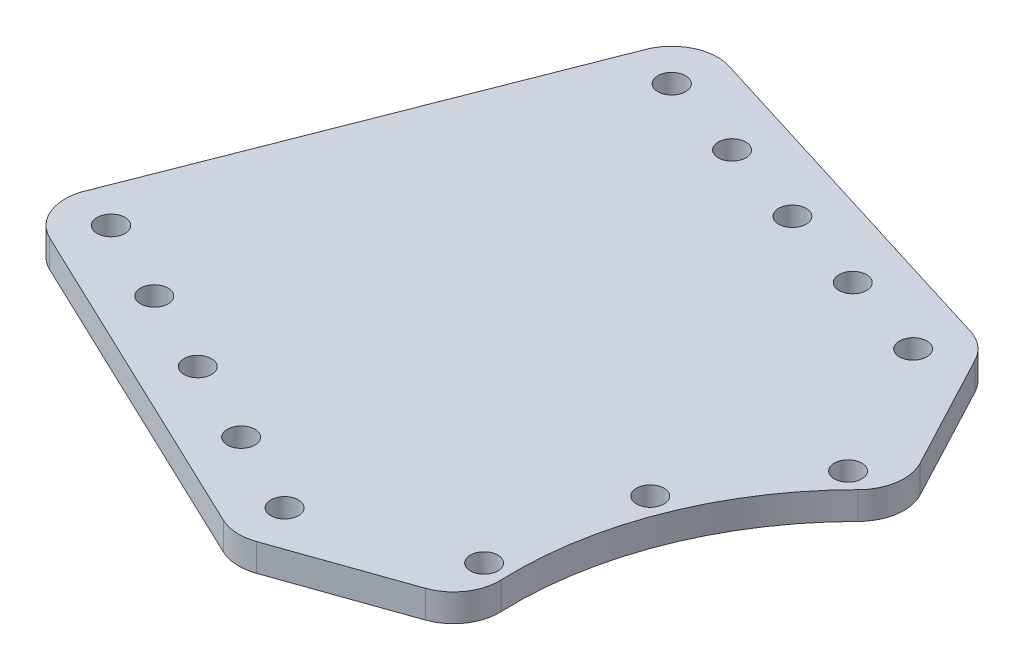
SolidWorks part; units mm, degrees
ref_plane "前视基准面" through (0, 0, 0) normal (0, 0, 1) x (1, 0, 0)
ref_plane "上视基准面" through (0, 0, 0) normal (0, 1, 0) x (1, 0, 0)
ref_plane "右视基准面" through (0, 0, 0) normal (1, 0, 0) x (0, 0, -1)
other "Configuration Table"
sketch "草图2" plane through (0, -12.8, 0) normal (0, 1, 0) x (1, 0, 0)
  line L1 (-67.7502, -36.977) -> (-103.859, -19.7974)
  line L3 (-106.2324, -13.116) -> (-89.1855, 30.4759)
  line L4 (-83.0443, 33.4294) -> (-44.8604, 21.5564)
  line L5 (-41.9259, 19.121) -> (-35.1765, 6.3696)
  line L6 (-50.333, -32.3883) -> (-63.942, -37.1784)
  arc A0 (-103.859, -19.7974) -> (-106.2324, -13.116) centre (-101.7049, -15.27) cw
  arc A1 (-89.1855, 30.4759) -> (-83.0443, 33.4294) centre (-84.5289, 28.6549) cw
  arc A2 (-44.8604, 21.5564) -> (-41.9259, 19.121) centre (-46.345, 16.7819) cw
  arc A3 (-35.1765, 6.3696) -> (-36.058, 0.4971) centre (-39.5956, 4.0306) cw
  arc A4 (-36.058, 0.4971) -> (-46.9969, -27.4757) centre (-9.5258, -26.0037) ccw
  arc A5 (-46.9969, -27.4757) -> (-50.333, -32.3883) centre (-51.993, -27.6719) cw
  arc A6 (-63.942, -37.1784) -> (-67.7502, -36.977) centre (-65.6021, -32.462) cw
  circle A7 centre (-65.6021, -32.462) radius 1.5
  circle A8 centre (-74.6321, -28.1657) radius 1.5
  circle A9 centre (-83.6622, -23.8695) radius 1.5
  circle A10 centre (-92.6923, -19.5732) radius 1.5
  circle A11 centre (-101.7049, -15.27) radius 1.5187
  circle A12 centre (-84.5289, 28.6549) radius 1.5127
  circle A13 centre (-74.9921, 25.6895) radius 1.5
  circle A14 centre (-65.443, 22.7203) radius 1.5
  circle A15 centre (-55.894, 19.7511) radius 1.5
  circle A16 centre (-46.345, 16.7819) radius 1.5
  circle A17 centre (-38.368, 1.7114) radius 1.5
  circle A18 centre (-46.7787, -11.4358) radius 1.5
  circle A19 centre (-49.5179, -26.8007) radius 1.5
extrude "凸台-拉伸1" add sketch "草图2" along normal blind 3
